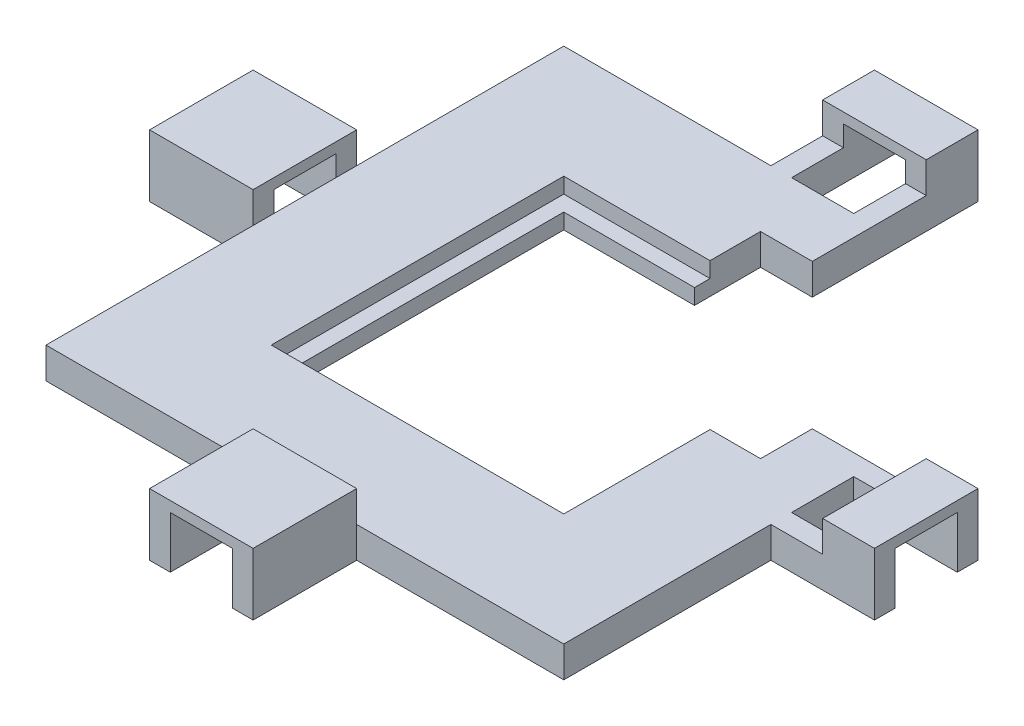
SolidWorks part; units mm, degrees
ref_plane "Front Plane" through (0, 0, 0) normal (0, 0, 1) x (1, 0, 0)
ref_plane "Top Plane" through (0, 0, 0) normal (0, 1, 0) x (1, 0, 0)
ref_plane "Right Plane" through (0, 0, 0) normal (1, 0, 0) x (0, 0, -1)
sketch "Sketch1" plane through (0, 0, 0) normal (0, 1, 0) x (1, 0, 0)
  line L0 (-50, 50) -> (-10, 50)
  line L1 (-10, 50) -> (-10, 70)
  line L2 (-10, -70) -> (10, -70)
  line L3 (-70, -10) -> (-70, 10)
  line L4 (-10, 70) -> (10, 70)
  line L7 (10, 70) -> (10, 25.25)
  line L8 (10, 25.25) -> (-25.25, 25.25)
  line L9 (-25.25, 25.25) -> (-25.25, -25.25)
  line L10 (25.25, 10) -> (70, 10)
  line L11 (70, 10) -> (70, -10)
  line L16 (70, -10) -> (50, -10)
  line L17 (50, -10) -> (50, -50)
  line L18 (50, -50) -> (10, -50)
  line L19 (10, -50) -> (10, -70)
  line L25 (-10, -70) -> (-10, -50)
  line L26 (-10, -50) -> (-50, -50)
  line L27 (-50, -50) -> (-50, -10)
  line L28 (-50, -10) -> (-70, -10)
  line L34 (-70, 10) -> (-50, 10)
  line L35 (-50, 10) -> (-50, 50)
  line L36 (-25.25, -25.25) -> (25.25, -25.25)
  line L37 (25.25, -25.25) -> (25.25, 10)
extrude "Boss-Extrude10" add sketch "Sketch1" along normal blind 12 contours L8 L9 L36 L37 L10 L11 L16 L17 L18 L19 L2 L25 L26 L27 L28 L3 L34 L35 L0 L1 L4 L7
sketch "Sketch6" plane through (0, 12, 0) normal (0, 1, 0) x (1, 0, 0)
  line L0 (50, -10) -> (50, -50) construction
  line L1 (-50, 50) -> (50, 50)
  line L2 (-50, 50) -> (-50, -50)
  line L3 (-50, -50) -> (50, -50)
  line L4 (50, 50) -> (50, -50)
extrude "Cut-Extrude1" cut sketch "Sketch6" against normal blind 6
sketch "Sketch7" plane through (0, 0, 0) normal (0, -1, 0) x (-1, 0, 0)
  line L0 (70, -10) -> (70, 10) construction
  line L1 (70, -6) -> (50, -6)
  line L2 (70, -6) -> (70, 6)
  line L3 (70, 6) -> (50, 6)
  line L4 (50, -6) -> (50, 6)
  line L5 (10, -70) -> (-10, -70) construction
  line L6 (6, -70) -> (-6, -70)
  line L7 (6, -70) -> (6, -50)
  line L8 (6, -50) -> (-6, -50)
  line L9 (-6, -70) -> (-6, -50)
  line L10 (-70, 10) -> (-70, -10) construction
  line L11 (-70, -6) -> (-50, -6)
  line L12 (-70, -6) -> (-70, 6)
  line L13 (-70, 6) -> (-50, 6)
  line L14 (-50, -6) -> (-50, 6)
  line L15 (10, 70) -> (-10, 70) construction
  line L16 (-6, 70) -> (6, 70)
  line L17 (-6, 70) -> (-6, 50)
  line L18 (-6, 50) -> (6, 50)
  line L19 (6, 70) -> (6, 50)
extrude "Cut-Extrude2" cut sketch "Sketch7" against normal blind 10
sketch "Sketch8" plane through (0, 6, 0) normal (0, 1, 0) x (1, 0, 0)
  line L1 (-28.25, 28.25) -> (28.25, 28.25)
  line L2 (-28.25, 28.25) -> (-28.25, -28.25)
  line L3 (-28.25, -28.25) -> (28.25, -28.25)
  line L4 (28.25, 28.25) -> (28.25, -28.25)
extrude "Cut-Extrude3" cut sketch "Sketch8" against normal blind 3
sketch "Sketch10" plane through (0, 12, 0) normal (0, 1, 0) x (1, 0, 0)
  line L0 (-10, 50) -> (-10, 70) construction
  line L1 (-10, 60) -> (10, 60)
  line L2 (-10, 60) -> (-10, 50)
  line L3 (-10, 50) -> (10, 50)
  line L4 (10, 60) -> (10, 50)
  line L5 (50, 10) -> (70, 10) construction
  line L6 (60, 10) -> (50, 10)
  line L7 (60, 10) -> (60, -10)
  line L8 (60, -10) -> (50, -10)
  line L9 (50, 10) -> (50, -10)
extrude "Cut-Extrude6" cut sketch "Sketch10" against normal blind 6
sketch "Sketch11" plane through (0, 6, 0) normal (0, 1, 0) x (1, 0, 0)
  line L0 (10, 60) -> (10, 28.25) construction
  line L1 (10, 38) -> (0, 38)
  line L2 (10, 38) -> (10, 25.25)
  line L3 (10, 25.25) -> (0, 25.25)
  line L4 (0, 38) -> (0, 25.25)
  line L5 (10, 25.25) -> (-25.25, 25.25) construction
  line L6 (28.25, 10) -> (60, 10) construction
  line L7 (38, 10) -> (25.25, 10)
  line L8 (38, 10) -> (38, 0)
  line L9 (38, 0) -> (25.25, 0)
  line L10 (25.25, 10) -> (25.25, 0)
  line L11 (25.25, -25.25) -> (25.25, 10) construction
extrude "Cut-Extrude7" cut sketch "Sketch11" against normal through all
